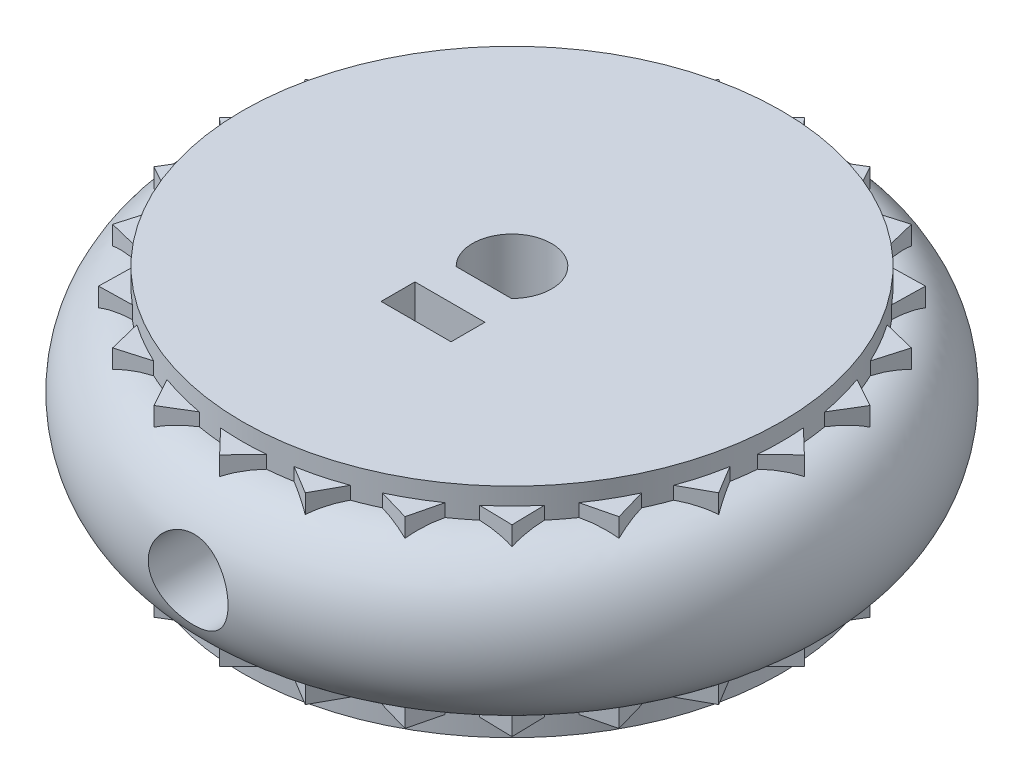
SolidWorks part; units mm, degrees
material "ABS"
ref_plane "Front Plane" through (0, 0, 0) normal (0, 0, 1) x (1, 0, 0)
ref_plane "Top Plane" through (0, 0, 0) normal (0, 1, 0) x (1, 0, 0)
ref_plane "Right Plane" through (0, 0, 0) normal (1, 0, 0) x (0, 0, -1)
sketch "Sketch1" plane through (0, 0, 0) normal (1, 0, 0) x (0, 0, -1)
  line L0 (0, 0) -> (23.876, 0)
  line L1 (23.876, 0) -> (23.876, 19.304)
  line L2 (23.876, 19.304) -> (0, 19.304)
  line L3 (0, 19.304) -> (0, 0)
  line L4 (23.876, 9.652) -> (29.21, 9.652)
  ellipse E0 centre (23.876, 9.652) end of major axis (23.876, 2.667) minor radius 5.334 (23.876, 2.667) -> (23.876, 16.637) ccw
  dimension "D5" = 5.334
  dimension "D1" = 23.876
  dimension "D2" = 19.304
  dimension "D3" = 13.97
revolve "Revolve1" add sketch "Sketch1" angle 360 about L3
sketch "Sketch2" plane through (0, 0, 0) normal (0, -1, 0) x (1, 0, 0)
  line L0 (-2.4495, 2.5) -> (2.4495, 2.5)
  line L2 (-3.1, 5.5) -> (3.1, 5.5)
  line L3 (-3.1, 5.5) -> (-3.1, 8.5)
  line L4 (-3.1, 8.5) -> (3.1, 8.5)
  line L5 (3.1, 5.5) -> (3.1, 8.5)
  arc A0 (-2.4495, 2.5) -> (2.4495, 2.5) centre (0, 0) ccw
  point P8 (0, 5.5)
  point P9 (0, 2.5)
  dimension "D1" = 7
  dimension "D2" = 2.5
  dimension "D3" = 6.2
  dimension "D4" = 3
  dimension "D5" = 3
extrude "Cut-Extrude1" cut sketch "Sketch2" against normal through all
ref_plane "Plane1" through (0, 0, 33.9) normal (0, 0, -1) x (-1, 0, 0)
sketch "Sketch3" plane through (0, 0, 33.9) normal (0, 0, -1) x (-1, 0, 0)
  line L0 (-3.1, 19.304) -> (-3.1, 0) construction
  line L1 (3.1, 19.304) -> (-3.1, 19.304) construction
  circle A0 centre (-0.3, 9.652) radius 2
  dimension "D3" = 4
  dimension "D1" = 2.8
  dimension "D2" = 9.652
extrude "Cut-Extrude2" cut sketch "Sketch3" along normal blind 33.528 contours A0
ref_plane "Plane2" through (0, 17.78, 0) normal (0, 1, 0) x (1, 0, 0)
sketch "Sketch5" plane through (0, 17.78, 0) normal (0, 1, 0) x (1, 0, 0)
  line L0 (0, -23.876) -> (0, -25.908)
  line L1 (0, -25.908) -> (2.032, -23.7894)
  line L2 (0, -25.908) -> (-2.032, -23.7894)
  circle A0 centre (0, 0) radius 23.876
  circle A1 centre (0, 0) radius 23.876 construction
  dimension "D1" = 2.032
  dimension "D2" = 4.064
  dimension "D3" = 2.032
extrude "Boss-Extrude1" add sketch "Sketch5" against normal blind 16.256 contours A0 L0 L1 | A0 L2 L0
sketch "Sketch4" plane through (0, 0, 33.9) normal (0, 0, -1) x (-1, 0, 0)
  circle A0 centre (-0.3, 9.652) radius 3.5
  circle A1 centre (-0.3, 9.652) radius 2 construction
  dimension "D1" = 7
extrude "Cut-Extrude3" cut sketch "Sketch4" along normal blind 22.86 contours A0
pattern_circular "CirPattern1" count 24 every 15 about axis through (0, 0, 0) along (0, 1, 0) of "Boss-Extrude1"
ref_plane "Plane3" through (0, 9.652, 0) normal (0, 1, 0) x (1, 0, 0)
